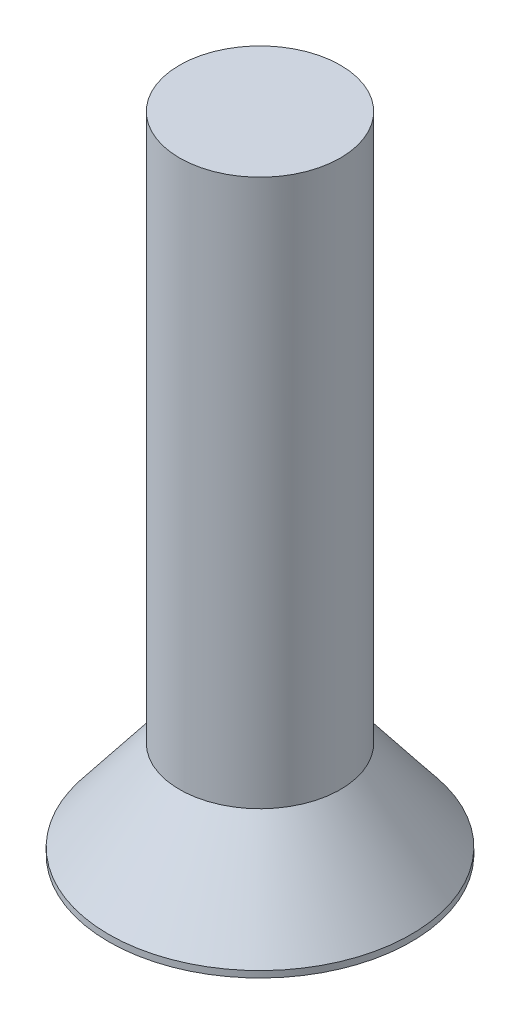
SolidWorks part; units mm, degrees
material "AISI 304"
ref_plane "Front Plane" through (0, 0, 0) normal (0, 0, 1) x (1, 0, 0)
ref_plane "Top Plane" through (0, 0, 0) normal (0, 1, 0) x (1, 0, 0)
ref_plane "Right Plane" through (0, 0, 0) normal (1, 0, 0) x (0, 0, -1)
sketch "Sketch1" plane through (0, 0, 0) normal (0, 1, 0) x (1, 0, 0)
  circle A0 centre (0, 0) radius 1.25
  dimension "D1" = 2.5
extrude "Boss-Extrude1" add sketch "Sketch1" along normal blind 10
sketch "Sketch2" plane through (0, 0, 0) normal (1, 0, 0) x (0, 0, -1)
  line L0 (0, 0) -> (0, 1.5)
  line L1 (0, 1.5) -> (-1.25, 1.5)
  line L2 (-1.25, 10) -> (-1.25, 0) construction
  line L3 (-1.25, 1.5) -> (-2.35, 0.1)
  line L4 (-2.35, 0) -> (0, 0)
  line L5 (-2.35, 0.1) -> (-2.35, 0)
  point P4 (0, 0)
  dimension "D1" = 2.35
  dimension "D2" = 1.5
  dimension "D3" = 0.1
ref_axis "Axis1" through (0, -0.5, 0) along (0, 1, 0)
revolve "Revolve1" add sketch "Sketch2" angle 360 about axis through (0, -0.5, 0) along (0, 1, 0)
sketch "Sketch3" plane through (0, 0, 0) normal (0, -1, 0) x (1, 0, 0)
  line L0 (-1.5, -0.25) -> (-0.25, -0.25)
  line L1 (1.5, -0.25) -> (-1.5, -0.25) construction
  line L2 (1.5, -0.25) -> (1.5, 0.25) construction
  line L3 (1.5, 0.25) -> (-1.5, 0.25) construction
  line L4 (-1.5, -0.25) -> (-1.5, 0.25) construction
  line L5 (1.5, -0.25) -> (-1.5, 0.25) construction
  line L6 (1.5, 0.25) -> (-1.5, -0.25) construction
  line L7 (-0.25, -1.5) -> (0.25, -1.5) construction
  line L8 (-0.25, -1.5) -> (-0.25, 1.5) construction
  line L9 (-0.25, 1.5) -> (0.25, 1.5) construction
  line L10 (0.25, -1.5) -> (0.25, 1.5) construction
  line L11 (-0.25, -1.5) -> (0.25, 1.5) construction
  line L12 (-0.25, 1.5) -> (0.25, -1.5) construction
  line L13 (-0.25, -0.25) -> (-0.25, -1.5)
  line L14 (-0.25, -1.5) -> (0.25, -1.5)
  line L15 (0.25, -1.5) -> (0.25, -0.25)
  line L16 (0.25, -0.25) -> (1.5, -0.25)
  line L17 (1.5, -0.25) -> (1.5, 0.25)
  line L18 (1.5, 0.25) -> (0.25, 0.25)
  line L19 (0.25, 0.25) -> (0.25, 1.5)
  line L20 (0.25, 1.5) -> (-0.25, 1.5)
  line L21 (-0.25, 1.5) -> (-0.25, 0.25)
  line L22 (-0.25, 0.25) -> (-1.5, 0.25)
  line L23 (-1.5, 0.25) -> (-1.5, -0.25)
  point P0 (0, 0)
  point P6 (0, 0)
  dimension "D1" = 0.5
  dimension "D2" = 3
extrude "Cut-Extrude1" cut sketch "Sketch3" against normal blind 0.5
